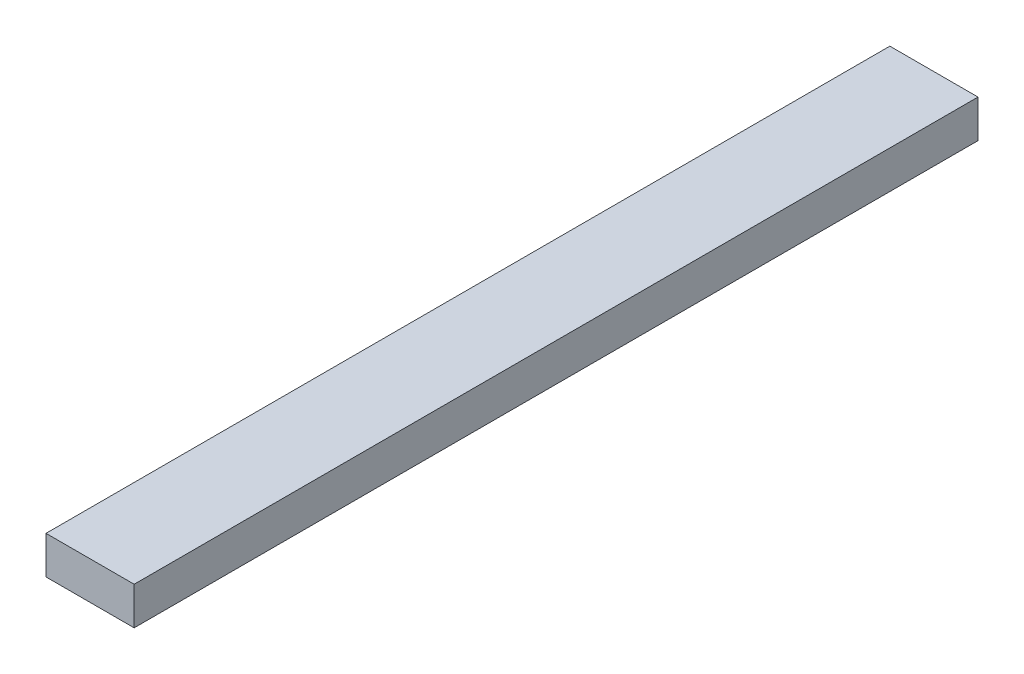
SolidWorks part; units mm, degrees
material "Pine"
ref_plane "Front Plane" through (0, 0, 0) normal (0, 0, 1) x (1, 0, 0)
ref_plane "Top Plane" through (0, 0, 0) normal (0, 1, 0) x (1, 0, 0)
ref_plane "Right Plane" through (0, 0, 0) normal (1, 0, 0) x (0, 0, -1)
sketch "Sketch1" plane through (0, 0, 0) normal (0, 0, 1) x (1, 0, 0)
  line L1 (0, 0) -> (88.9, 0)
  line L2 (0, 0) -> (0, 38.1)
  line L3 (0, 38.1) -> (88.9, 38.1)
  line L4 (88.9, 0) -> (88.9, 38.1)
  dimension "D1" = 88.9
  dimension "D2" = 38.1
extrude "Boss-Extrude1" add sketch "Sketch1" along normal blind 850.9
sketch "Sketch2" plane through (0, 0, 0) normal (0, 0, -1) x (-1, 0, 0)
  line L1 (-88.9, 0) -> (-88.9, 38.1) construction
  line L2 (0, 38.1) -> (0, 0) construction
  line L3 (-44.45, 19.05) -> (-88.9, 19.05) construction
  line L4 (-44.45, 19.05) -> (0, 19.05) construction
  circle A0 centre (-66.675, 19.05) radius 0.8763
  circle A1 centre (-22.225, 19.05) radius 0.8763
  dimension "D1" = 1.7526
sketch "Sketch3" plane through (0, 0, 0) normal (0, -1, 0) x (1, 0, 0)
  line L0 (44.45, 850.9) -> (44.45, 806.45) construction
  line L1 (0, 850.9) -> (88.9, 850.9) construction
  line L2 (44.45, 806.45) -> (44.45, 762) construction
  line L3 (88.9, 425.45) -> (0, 425.45) construction
  line L4 (88.9, 850.9) -> (88.9, 0) construction
  line L5 (0, 850.9) -> (0, 0) construction
  line L6 (44.45, 425.45) -> (44.45, 469.9) construction
  line L7 (44.45, 425.45) -> (44.45, 381) construction
  circle A0 centre (44.45, 828.675) radius 0.8763
  circle A1 centre (44.45, 784.225) radius 0.8763
  circle A2 centre (44.45, 22.225) radius 0.8763
  circle A3 centre (44.45, 66.675) radius 0.8763
  circle A4 centre (44.45, 403.225) radius 0.8763
  circle A5 centre (44.45, 447.675) radius 0.8763
  dimension "D2" = 1.7526
  dimension "D4" = 1.7526
  dimension "D1" = 88.9
  dimension "D3" = 88.9
equation "\"length\"= 20"
equation "\"length\"= 22"
equation "\"length\"= 36"
equation "\"length\"= 26"
equation "\"length\"= 27"
equation "\"length\"= 28"
equation "\"length\"= 39"
equation "\"length\"= 96"
equation "\"length\"= 30"
equation "\"length\"= 32"
